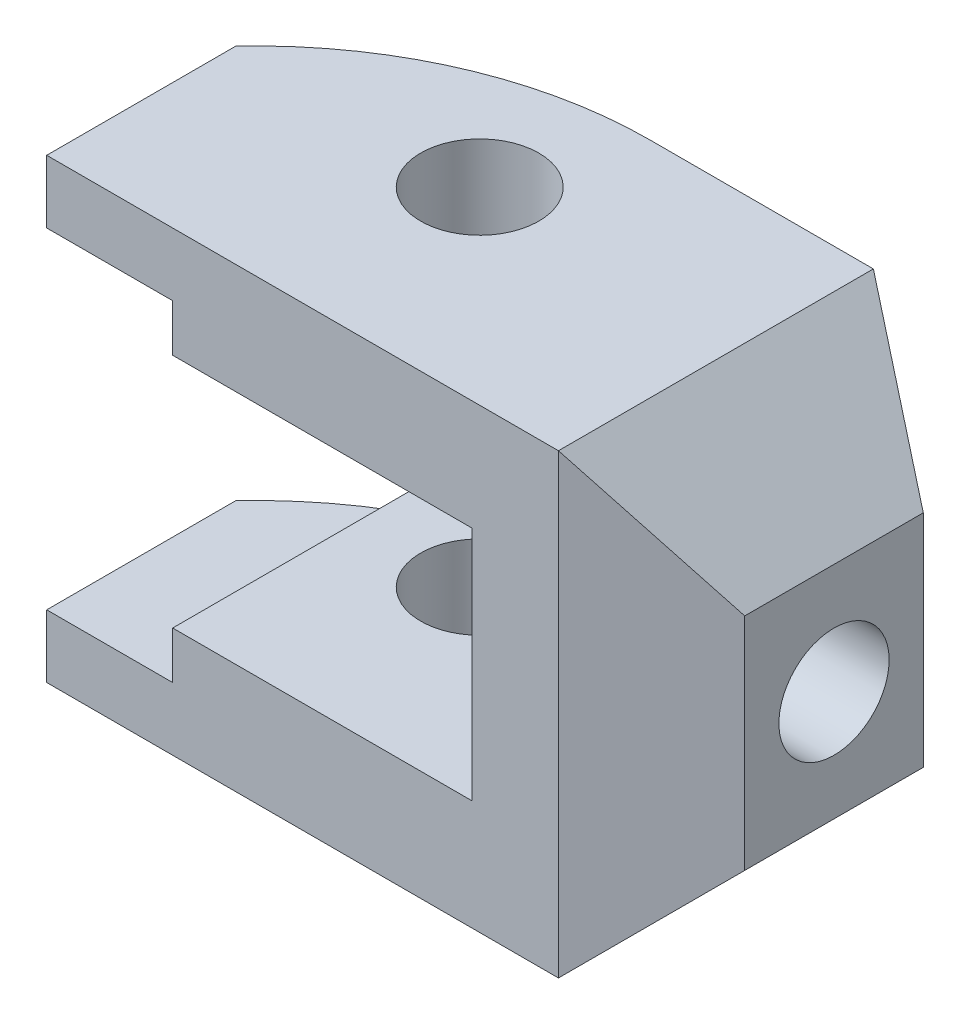
SolidWorks part; units mm, degrees
material "Alliage 1060"
ref_plane "Plan de face" through (0, 0, 0) normal (0, 0, 1) x (1, 0, 0)
ref_plane "Plan de dessus" through (0, 0, 0) normal (0, 1, 0) x (1, 0, 0)
ref_plane "Plan de droite" through (0, 0, 0) normal (1, 0, 0) x (0, 0, -1)
sketch "Esquisse1" plane through (0, 0, 0) normal (0, 1, 0) x (1, 0, 0)
  line L0 (0, 0) -> (65, 0)
  line L1 (65, 0) -> (80, 8.6603)
  line L5 (0, 0) -> (0, 24)
  line L6 (80, 8.6603) -> (80, 31.3397)
  line L9 (65, 40) -> (80, 31.3397)
  line L10 (65, 40) -> (135.5224, 40) construction
  line L11 (65, 0) -> (24.9329, 0) construction
  line L12 (0, 24) -> (31, 24) construction
  line L13 (65, 40) -> (36.6606, 40)
  circle A1 centre (31, 24) radius 7.5
  arc A2 (36.6606, 40) -> (0, 24) centre (36.6606, -10) ccw
  dimension "D3" = 50
  dimension "D9" = 15
  dimension "D2" = 24
  dimension "D4" = 15
  dimension "D5" = 30
  dimension "D6" = 15
  dimension "D7" = 30
  dimension "D8" = 40
  dimension "D1" = 65
extrude "Boss.-Extru.1" add sketch "Esquisse1" along normal blind 58
sketch "Esquisse2" plane through (0, 0, 0) normal (0, 0, 1) x (1, 0, 0)
  line L0 (0, 58) -> (0, 0) construction
  line L1 (0, 44) -> (54, 44)
  line L2 (0, 44) -> (0, 14)
  line L3 (0, 14) -> (54, 14)
  line L4 (54, 44) -> (54, 14)
  dimension "D1" = 11
  dimension "D2" = 14
  dimension "D3" = 14
extrude "Enlèv. mat.-Extru.1" cut sketch "Esquisse2" against normal through all
sketch "Esquisse3" plane through (0, 0, 0) normal (0, 0, 1) x (1, 0, 0)
  line L0 (0, 58) -> (0, 44) construction
  line L1 (0, 50) -> (16, 50)
  line L2 (0, 50) -> (0, 8)
  line L3 (0, 8) -> (16, 8)
  line L4 (16, 50) -> (16, 8)
  dimension "D1" = 8
  dimension "D2" = 8
  dimension "D3" = 16
extrude "Enlèv. mat.-Extru.2" cut sketch "Esquisse3" against normal through all
sketch "Esquisse5" plane through (0, 0, -40) normal (0, 0, -1) x (-1, 0, 0)
  line L0 (-65, 58) -> (-80, 58)
  line L1 (-80, 58) -> (-80, 43)
  line L2 (-80, 58) -> (-80, 0) construction
  line L3 (-80, 43) -> (-65, 58)
  line L7 (-65, 0) -> (-80, 0)
  line L8 (-80, 0) -> (-80, 15)
  line L9 (-80, 15) -> (-65, 0)
  dimension "D1" = 45
  dimension "D2" = 45
extrude "Enlèv. mat.-Extru.4" cut sketch "Esquisse5" against normal through all
sketch "Esquisse6" plane through (80, 0, 0) normal (1, 0, 0) x (0, 0, -1)
  line L0 (40, 58) -> (40, 0) construction
  circle A0 centre (20, 29) radius 7
  point P6 (72.3753, 59.1558)
  dimension "D1" = 20
  dimension "D2" = 29
extrude "Enlèv. mat.-Extru.6" cut sketch "Esquisse6" against normal through all
equation "\"c\"= 65mm"
equation "\"a\"= 58mm"
equation "\"b\"= 40mm"
equation "\"D8@Esquisse1\"=\"b\""
equation "\"D1@Esquisse1\"=\"c\""
equation "\"D1@Esquisse6\"=\"b\"/2"
equation "\"D2@Esquisse6\"=\"a\"/2"
